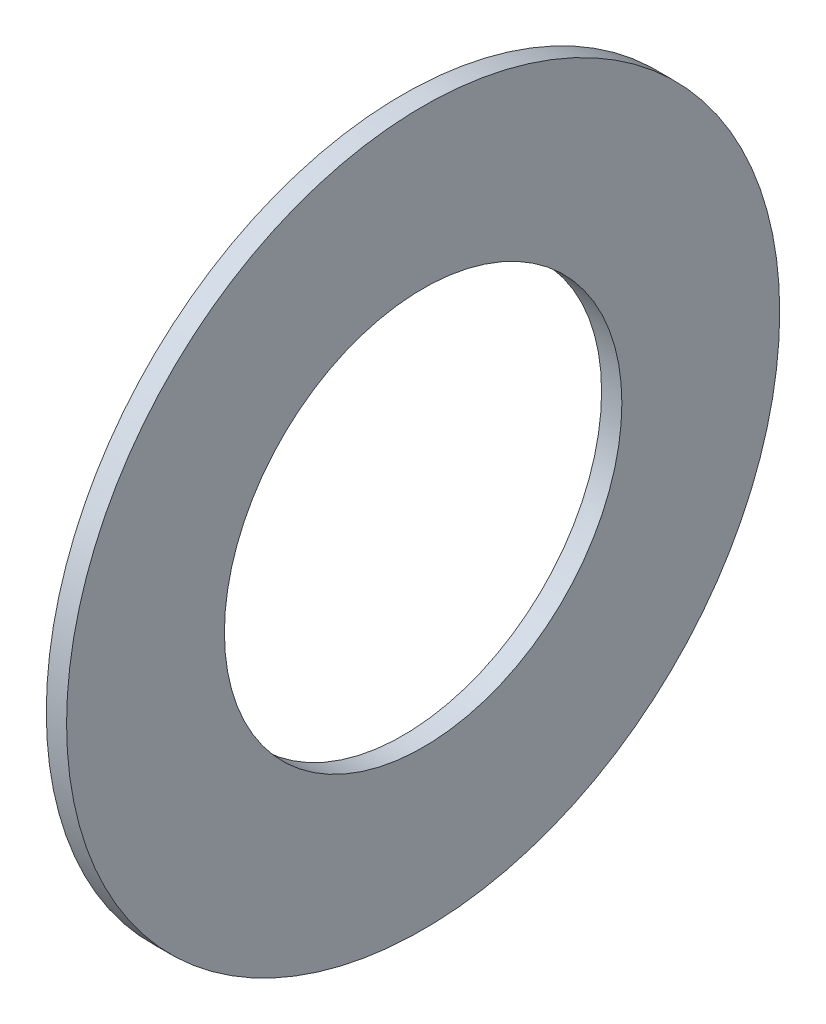
SolidWorks part; units mm, degrees
ref_plane "Front Plane" through (0, 0, 0) normal (0, 0, 1) x (1, 0, 0)
ref_plane "Top Plane" through (0, 0, 0) normal (0, 1, 0) x (1, 0, 0)
ref_plane "Right Plane" through (0, 0, 0) normal (1, 0, 0) x (0, 0, -1)
sketch "Sketch1" plane through (0, 0, 0) normal (1, 0, 0) x (0, 0, -1)
  line L0 (7.9375, 0) -> (-7.9375, 0) construction
  circle A0 centre (0, 0) radius 14.2875 construction
  circle A1 centre (0, 0) radius 7.9629 construction
  circle A2 centre (0, 0) radius 7.9375
  point P9 (0, 0)
  dimension "OD" = 28.575
  dimension "ID" = 15.9258
  dimension "For Shaft Diameter" = 15.875
sketch "Sketch2" plane through (0, 0, 0) normal (0, 0, 1) x (1, 0, 0)
  line L0 (0.4064, 0) -> (-0.4064, 0) construction
  line L2 (0.4064, -14.2875) -> (-0.4064, -14.2875) construction
  line L3 (0.4064, -14.2875) -> (0.4064, 14.2875) construction
  line L4 (0.4064, 14.2875) -> (-0.4064, 14.2875) construction
  line L5 (-0.4064, -14.2875) -> (-0.4064, 14.2875) construction
  line L6 (0, 14.2875) -> (0, -14.2875) construction
  line L7 (0.4064, 0) -> (-0.4064, 0) construction
  line L8 (0, -14.2875) -> (0, 14.2875) construction
  point P0 (0, 0)
  point P4 (0, 0)
  dimension "Thickness" = 0.8128
  dimension "D1" = 28.575
sketch "Sketch5" plane through (0, 0, 0) normal (1, 0, 0) x (0, 0, -1)
  circle A0 centre (0, 0) radius 7.9629 construction
  circle A1 centre (0, 0) radius 14.2875 construction
  circle A3 centre (0, 0) radius 7.9629
  circle A5 centre (0, 0) radius 14.2875
extrude "Boss-Extrude1" add sketch "Sketch5" along normal mid plane 0.8128
equation "\"D1@Boss-Extrude1\"= \"Thickness@Sketch2\""
equation "\"D1@Sketch2\"=\"OD@Sketch1\""
